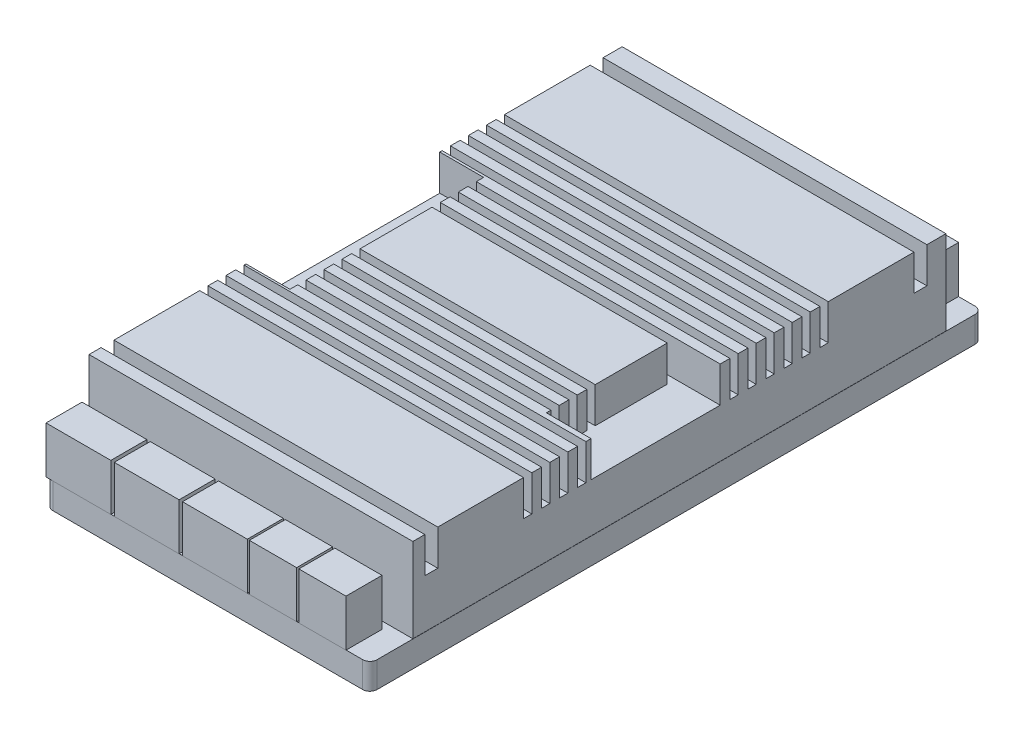
SolidWorks part; units mm, degrees
ref_plane "Ön Düzlem" through (0, 0, 0) normal (0, 0, 1) x (1, 0, 0)
ref_plane "Üst Düzlem" through (0, 0, 0) normal (0, 1, 0) x (1, 0, 0)
ref_plane "Sağ Düzlem" through (0, 0, 0) normal (1, 0, 0) x (0, 0, -1)
sketch "Sketch1" plane through (0, 0, 0) normal (0, 1, 0) x (1, 0, 0)
  line L1 (43, -85) -> (-43, -85)
  line L2 (45, -83) -> (45, 83)
  line L3 (43, 85) -> (-43, 85)
  line L4 (-45, -83) -> (-45, 83)
  line L5 (45, -85) -> (-45, 85) construction
  line L6 (45, 85) -> (-45, -85) construction
  arc A0 (43, -85) -> (45, -83) centre (43, -83) ccw
  arc A1 (-43, -85) -> (-45, -83) centre (-43, -83) cw
  arc A2 (45, 83) -> (43, 85) centre (43, 83) ccw
  arc A3 (-43, 85) -> (-45, 83) centre (-43, 83) ccw
  point P0 (0, 0)
  dimension "D3" = 2
  dimension "D1" = 90
  dimension "D2" = 170
extrude "Boss-Extrude1" add sketch "Sketch1" along normal blind 7.2
sketch "Sketch2" plane through (0, 7.2, 0) normal (0, 1, 0) x (1, 0, 0)
  line L1 (44.95, -73.0239) -> (-44.95, -73.0239)
  line L2 (44.95, -73.0239) -> (44.95, 74.9761)
  line L3 (44.95, 74.9761) -> (-44.95, 74.9761)
  line L4 (-44.95, -73.0239) -> (-44.95, 74.9761)
  line L7 (45, -83) -> (45, 83) construction
  point P0 (0, 0)
  dimension "D1" = 89.9
  dimension "D2" = 0.05
extrude "Boss-Extrude2" add sketch "Sketch2" along normal blind 23.4
sketch "Sketch3" plane through (0, 30.6, 0) normal (0, 1, 0) x (1, 0, 0)
  line L0 (-44.95, 74.9761) -> (-44.95, -73.0239) construction
  line L1 (-32.75, -29.4603) -> (-44.95, -29.4603)
  line L2 (-32.75, -29.4603) -> (-32.75, 24.3397)
  line L3 (-32.75, 24.3397) -> (-44.95, 24.3397)
  line L4 (-44.95, -29.4603) -> (-44.95, 24.3397)
  line L5 (-32.75, -29.4603) -> (-44.95, 24.3397) construction
  line L6 (-32.75, 24.3397) -> (-44.95, -29.4603) construction
  line L7 (44.95, -73.0239) -> (44.95, 74.9761) construction
  line L8 (32.55, 10.9089) -> (44.95, 10.9089)
  line L9 (32.55, 10.9089) -> (32.55, -23.5711)
  line L10 (32.55, -23.5711) -> (44.95, -23.5711)
  line L11 (44.95, 10.9089) -> (44.95, -23.5711)
  line L12 (32.55, 10.9089) -> (44.95, -23.5711) construction
  line L13 (32.55, -23.5711) -> (44.95, 10.9089) construction
  point P0 (-38.85, -2.5603)
  point P7 (38.75, -6.3311)
  dimension "D1" = 12.2
  dimension "D2" = 53.8
  dimension "D3" = 34.48
  dimension "D4" = 12.4
extrude "Cut-Extrude1" cut sketch "Sketch3" against normal blind 9.9
sketch "Sketch4" plane through (0, 30.6, 0) normal (0, 1, 0) x (1, 0, 0)
  line L0 (-44.95, 74.9761) -> (-44.95, 24.3397) construction
  line L1 (-44.95, 69.6884) -> (44.95, 69.6884)
  line L2 (-44.95, 69.6884) -> (-44.95, 66.1015)
  line L3 (-44.95, 66.1015) -> (44.95, 66.1015)
  line L4 (44.95, 69.6884) -> (44.95, 66.1015)
  line L5 (44.95, 10.9089) -> (44.95, 74.9761) construction
  line L6 (-50.3448, 0) -> (86.9824, 0) construction
  line L7 (45, -23.5711) -> (45, 10.9089) construction
  line L12 (45, 10) -> (-45, 10)
  line L13 (45, 10) -> (45, 12.2977)
  line L14 (45, 12.2977) -> (-45, 12.2977)
  line L15 (-45, 10) -> (-45, 12.2977)
  line L16 (-45, 24.3397) -> (-45, -29.4603) construction
  line L17 (45, 15) -> (-45, 15)
  line L18 (45, 15) -> (45, 17.2977)
  line L19 (45, 17.2977) -> (-45, 17.2977)
  line L20 (-45, 15) -> (-45, 17.2977)
  line L21 (45, 20) -> (-45, 20)
  line L22 (45, 20) -> (45, 22.2977)
  line L23 (45, 22.2977) -> (-45, 22.2977)
  line L24 (-45, 20) -> (-45, 22.2977)
  line L25 (45, 25) -> (-45, 25)
  line L26 (45, 25) -> (45, 27.2977)
  line L27 (45, 27.2977) -> (-45, 27.2977)
  line L28 (-45, 25) -> (-45, 27.2977)
  line L29 (45, 30) -> (-45, 30)
  line L30 (45, 30) -> (45, 32.2977)
  line L31 (45, 32.2977) -> (-45, 32.2977)
  line L32 (-45, 30) -> (-45, 32.2977)
  line L33 (45, 35) -> (-45, 35)
  line L34 (45, 35) -> (45, 37.2977)
  line L35 (45, 37.2977) -> (-45, 37.2977)
  line L36 (-45, 35) -> (-45, 37.2977)
  line L37 (45, 40) -> (-45, 40)
  line L38 (45, 40) -> (45, 42.2977)
  line L39 (45, 42.2977) -> (-45, 42.2977)
  line L40 (-45, 40) -> (-45, 42.2977)
  line L41 (-45, -40) -> (-45, -42.2977)
  line L42 (45, -42.2977) -> (-45, -42.2977)
  line L43 (45, -40) -> (45, -42.2977)
  line L44 (45, -40) -> (-45, -40)
  line L45 (-45, -35) -> (-45, -37.2977)
  line L46 (45, -37.2977) -> (-45, -37.2977)
  line L47 (45, -35) -> (45, -37.2977)
  line L48 (45, -35) -> (-45, -35)
  line L49 (-45, -30) -> (-45, -32.2977)
  line L50 (45, -32.2977) -> (-45, -32.2977)
  line L51 (45, -30) -> (45, -32.2977)
  line L52 (45, -30) -> (-45, -30)
  line L53 (-45, -25) -> (-45, -27.2977)
  line L54 (45, -27.2977) -> (-45, -27.2977)
  line L55 (45, -25) -> (45, -27.2977)
  line L56 (45, -25) -> (-45, -25)
  line L57 (-45, -20) -> (-45, -22.2977)
  line L58 (45, -22.2977) -> (-45, -22.2977)
  line L59 (45, -20) -> (45, -22.2977)
  line L60 (45, -20) -> (-45, -20)
  line L61 (-45, -15) -> (-45, -17.2977)
  line L62 (45, -17.2977) -> (-45, -17.2977)
  line L63 (45, -15) -> (45, -17.2977)
  line L64 (45, -15) -> (-45, -15)
  line L65 (-45, -10) -> (-45, -12.2977)
  line L66 (45, -12.2977) -> (-45, -12.2977)
  line L67 (45, -10) -> (45, -12.2977)
  line L68 (45, -10) -> (-45, -10)
  line L69 (44.95, -69.6884) -> (44.95, -66.1015)
  line L70 (-44.95, -66.1015) -> (44.95, -66.1015)
  line L71 (-44.95, -69.6884) -> (-44.95, -66.1015)
  line L72 (-44.95, -69.6884) -> (44.95, -69.6884)
  dimension "D1" = 10
  dimension "D2" = 7
extrude "Cut-Extrude2" cut sketch "Sketch4" against normal blind 9.9
sketch "Sketch5" plane through (0, 7.2, 0) normal (0, 1, 0) x (1, 0, 0)
  line L1 (-44.8708, -75.05) -> (-26.8708, -75.05)
  line L2 (-44.8708, -75.05) -> (-44.8708, -85.05)
  line L3 (-44.8708, -85.05) -> (-26.8708, -85.05)
  line L4 (-26.8708, -75.05) -> (-26.8708, -85.05)
  line L6 (-25.9225, -75.05) -> (-7.9225, -75.05)
  line L7 (-25.9225, -75.05) -> (-25.9225, -85.05)
  line L8 (-25.9225, -85.05) -> (-7.9225, -85.05)
  line L9 (-7.9225, -75.05) -> (-7.9225, -85.05)
  line L10 (-6.9742, -75.05) -> (11.0258, -75.05)
  line L11 (-6.9742, -75.05) -> (-6.9742, -85.05)
  line L12 (-6.9742, -85.05) -> (11.0258, -85.05)
  line L13 (11.0258, -75.05) -> (11.0258, -85.05)
  line L14 (-50.8837, 0) -> (68.4754, 0) construction
  line L15 (11.5851, -75.05) -> (24.7139, -75.05)
  line L16 (11.5851, -75.05) -> (11.5851, -85.05)
  line L17 (11.5851, -85.05) -> (24.7139, -85.05)
  line L18 (24.7139, -75.05) -> (24.7139, -85.05)
  line L19 (25.3256, -75.05) -> (38.4073, -75.05)
  line L20 (25.3256, -75.05) -> (25.3256, -85.05)
  line L21 (25.3256, -85.05) -> (38.4073, -85.05)
  line L22 (38.4073, -75.05) -> (38.4073, -85.05)
  line L43 (38.4073, 75.05) -> (38.4073, 85.05)
  line L44 (25.3256, 85.05) -> (38.4073, 85.05)
  line L45 (25.3256, 75.05) -> (25.3256, 85.05)
  line L46 (25.3256, 75.05) -> (38.4073, 75.05)
  line L47 (24.7139, 75.05) -> (24.7139, 85.05)
  line L48 (11.5851, 85.05) -> (24.7139, 85.05)
  line L49 (11.5851, 75.05) -> (11.5851, 85.05)
  line L50 (11.5851, 75.05) -> (24.7139, 75.05)
  line L51 (11.0258, 75.05) -> (11.0258, 85.05)
  line L52 (-6.9742, 85.05) -> (11.0258, 85.05)
  line L53 (-6.9742, 75.05) -> (-6.9742, 85.05)
  line L54 (-6.9742, 75.05) -> (11.0258, 75.05)
  line L55 (-7.9225, 75.05) -> (-7.9225, 85.05)
  line L56 (-25.9225, 85.05) -> (-7.9225, 85.05)
  line L57 (-25.9225, 75.05) -> (-25.9225, 85.05)
  line L58 (-25.9225, 75.05) -> (-7.9225, 75.05)
  line L59 (-26.8708, 75.05) -> (-26.8708, 85.05)
  line L60 (-44.8708, 85.05) -> (-26.8708, 85.05)
  line L61 (-44.8708, 75.05) -> (-44.8708, 85.05)
  line L62 (-44.8708, 75.05) -> (-26.8708, 75.05)
  dimension "D1" = 10
  dimension "D2" = 18
  dimension "D3" = 3
extrude "Boss-Extrude3" add sketch "Sketch5" along normal blind 13
